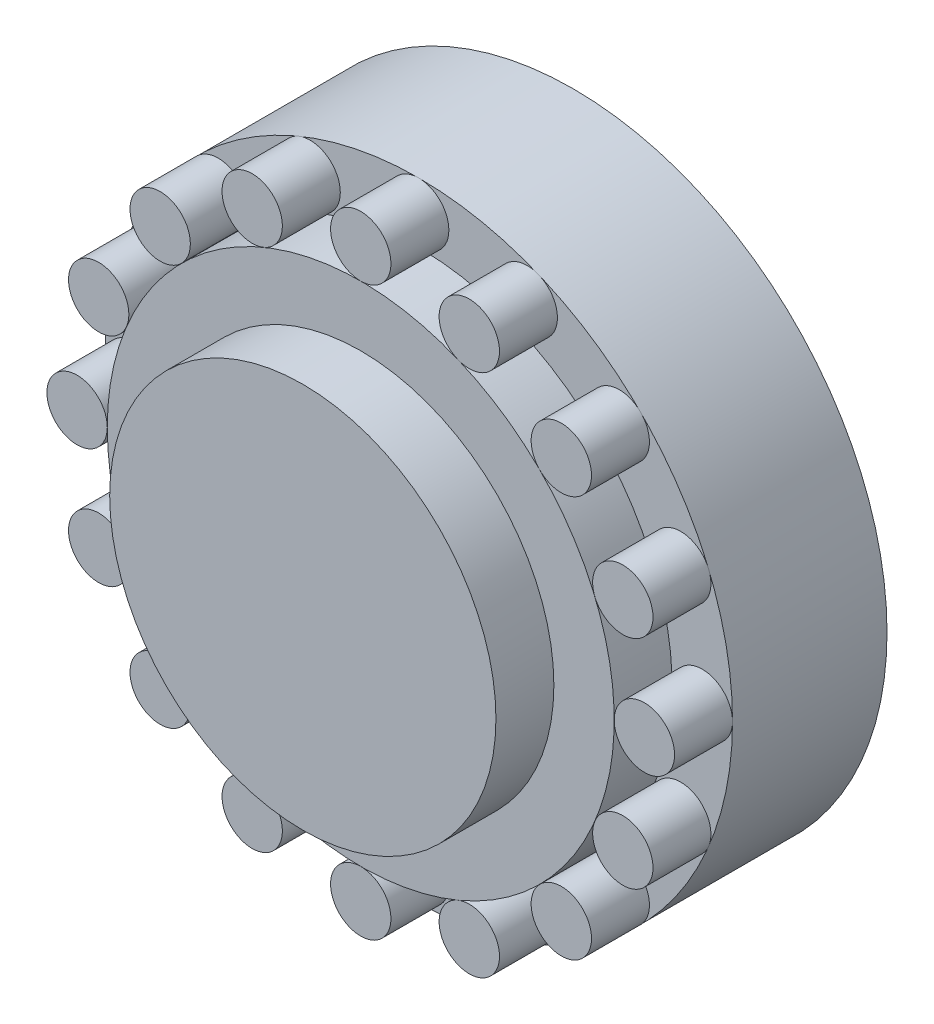
SolidWorks part; units mm, degrees
ref_plane "Piano frontale" through (0, 0, 0) normal (0, 0, 1) x (1, 0, 0)
ref_plane "Piano superiore" through (0, 0, 0) normal (0, 1, 0) x (1, 0, 0)
ref_plane "Piano destro" through (0, 0, 0) normal (1, 0, 0) x (0, 0, -1)
sketch "Schizzo1" plane through (0, 0, 0) normal (0, 1, 0) x (1, 0, 0)
  line L0 (0, 26.8311) -> (0, -28.0726) construction
  line L1 (0, 0) -> (32.5, 0)
  line L2 (32.5, 0) -> (32.5, -16)
  line L3 (32.5, -16) -> (0, -16)
  line L4 (26.25, -16) -> (26.25, -22)
  line L5 (26.25, -22) -> (0, -22)
  line L6 (20, -22) -> (20, -28)
  line L7 (20, -28) -> (0, -28)
  line L8 (0, 0) -> (0, -28)
  dimension "D1" = 32.5
  dimension "D2" = 16
  dimension "D3" = 6
  dimension "D4" = 26.25
  dimension "D5" = 6
  dimension "D6" = 20
revolve "Rivoluzione1" add sketch "Schizzo1" angle 360 about L0
sketch "Schizzo2" plane through (0, 0, 16) normal (0, 0, 1) x (1, 0, 0)
  line L0 (-32.5, 0) -> (32.5, 0) construction
  circle A0 centre (0, 0) radius 26.25 construction
  circle A1 centre (0, 0) radius 32.5 construction
  circle A2 centre (0, 0) radius 26.25 construction
  circle A3 centre (0, 0) radius 32.5 construction
  circle A4 centre (-29.375, 0) radius 3.125
  circle A5 centre (-27.139, 11.2412) radius 3.125
  circle A6 centre (-20.7714, 20.7711) radius 3.125
  circle A7 centre (-11.2415, 27.1388) radius 3.125
  circle A8 centre (-0.0003, 29.3748) radius 3.125
  circle A9 centre (11.2409, 27.1388) radius 3.125
  circle A10 centre (20.7708, 20.7712) radius 3.125
  circle A11 centre (27.1384, 11.2413) radius 3.125
  circle A12 centre (29.3745, 0.0001) radius 3.125
  circle A13 centre (27.1385, -11.2411) radius 3.125
  circle A14 centre (20.7709, -20.771) radius 3.125
  circle A15 centre (11.241, -27.1386) radius 3.125
  circle A16 centre (-0.0002, -29.3747) radius 3.125
  circle A17 centre (-11.2414, -27.1387) radius 3.125
  circle A18 centre (-20.7713, -20.7711) radius 3.125
  circle A19 centre (-27.139, -11.2412) radius 3.125
  circle A20 centre (0, 0) radius 29.375 construction
  point P41 (-0.0003, 0.0001)
  dimension "D2" = 11.2412
  dimension "D1" = 16
extrude "AgganciWeldingTorch" add sketch "Schizzo2" along normal blind 6 separate body
